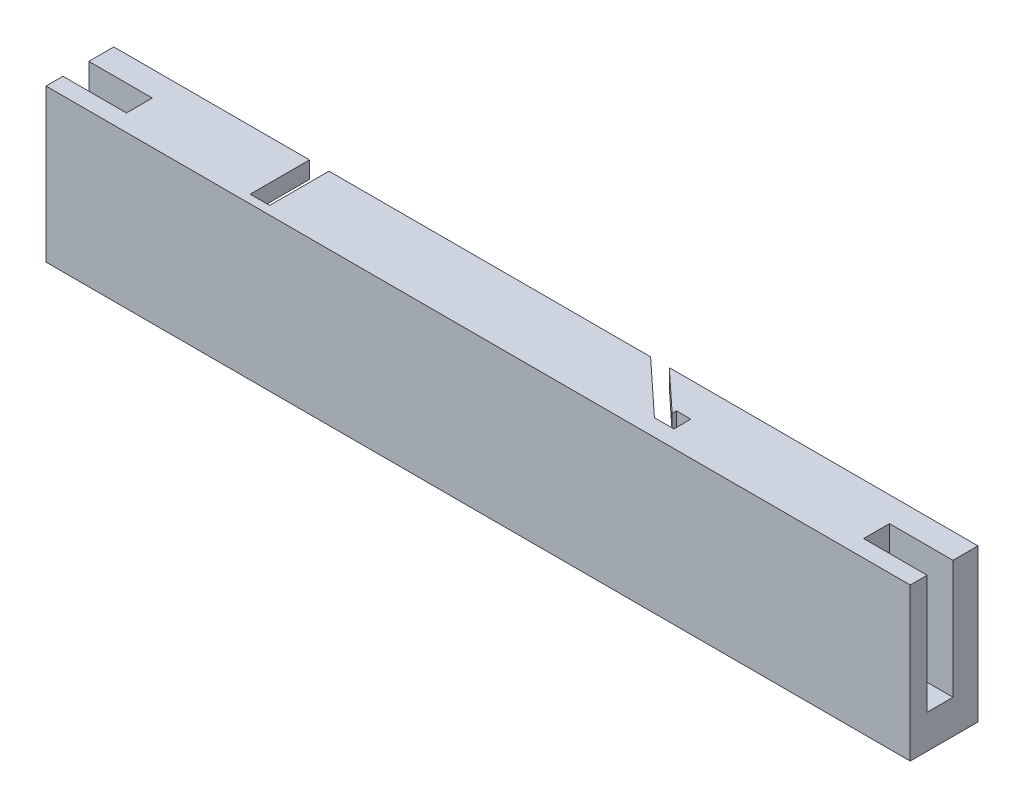
SolidWorks part; units mm, degrees
ref_plane "Front Plane" through (0, 0, 0) normal (0, 0, 1) x (1, 0, 0)
ref_plane "Top Plane" through (0, 0, 0) normal (0, 1, 0) x (1, 0, 0)
ref_plane "Right Plane" through (0, 0, 0) normal (1, 0, 0) x (0, 0, -1)
sketch "Sketch1" plane through (0, 0, 0) normal (0, 0, 1) x (1, 0, 0)
  line L1 (-51, -9) -> (51, -9)
  line L2 (-51, -9) -> (-51, 9)
  line L3 (-51, 9) -> (51, 9)
  line L4 (51, -9) -> (51, 9)
  line L5 (-51, -9) -> (51, 9) construction
  line L6 (-51, 9) -> (51, -9) construction
  point P0 (0, 0)
  dimension "D1" = 102
  dimension "D2" = 18
extrude "Boss-Extrude1" add sketch "Sketch1" along normal blind 2
sketch "Sketch2" plane through (0, 9, 0) normal (0, 1, 0) x (1, 0, 0)
  line L0 (0, -2) -> (0, 15.0089) construction
  line L1 (-51, -2) -> (-40.5, -2)
  line L2 (-51, -2) -> (-51, 6)
  line L3 (-51, 6) -> (-40.5, 6)
  line L4 (-40.5, -2) -> (-40.5, 6)
  line L5 (-51, 0) -> (-43.5, 0)
  line L6 (-51, 0) -> (-51, 3.05)
  line L7 (-51, 3.05) -> (-43.5, 3.05)
  line L8 (-43.5, 0) -> (-43.5, 3.05)
  line L9 (51, -2) -> (-51, -2) construction
  line L10 (43.5, 0) -> (43.5, 3.05)
  line L11 (51, 3.05) -> (43.5, 3.05)
  line L12 (51, 0) -> (51, 3.05)
  line L13 (51, 0) -> (43.5, 0)
  line L14 (40.5, -2) -> (40.5, 6)
  line L15 (51, 6) -> (40.5, 6)
  line L16 (51, -2) -> (51, 6)
  line L17 (51, -2) -> (40.5, -2)
  line M8 (51, 0) -> (-51, 0)
  dimension "D1" = 8
  dimension "D2" = 10.5
  dimension "D3" = 3.05
  dimension "D4" = 7.5
extrude "Boss-Extrude2" add sketch "Sketch2" against normal blind 18 contours L8 L4 L3 L2 L7 M8 | L11 L16 L15 L14 L10 M8
sketch "Sketch4" plane through (0, 0, 0) normal (0, 0, -1) x (-1, 0, 0)
  line L0 (40.5, -9) -> (40.5, 9) construction
  line L1 (-40.5, 9) -> (40.5, 9)
  line L2 (-40.5, 9) -> (-40.5, 7)
  line L3 (-40.5, 7) -> (40.5, 7)
  line L4 (40.5, 9) -> (40.5, 7)
  line L5 (40.5, -9) -> (40.5, 9) construction
  line L6 (-40.5, -9) -> (40.5, -9)
  line L7 (-40.5, -9) -> (-40.5, -7)
  line L8 (-40.5, -7) -> (40.5, -7)
  line L9 (40.5, -9) -> (40.5, -7)
  dimension "D1" = 2
  dimension "D2" = 2
extrude "Boss-Extrude3" add sketch "Sketch4" along normal blind 6
sketch "Sketch5" plane through (0, 0, -6) normal (0, 0, -1) x (-1, 0, 0)
  line L0 (40.5, -7) -> (-40.5, -7) construction
  line L1 (25.6, -7) -> (27.9, -7)
  line L2 (25.6, -7) -> (25.6, -9)
  line L3 (25.6, -9) -> (27.9, -9)
  line L4 (27.9, -7) -> (27.9, -9)
  line L5 (51, -9) -> (-51, -9) construction
  line L6 (51, -9) -> (51, 9) construction
  line L7 (-40.5, 7) -> (40.5, 7) construction
  line L8 (27.9, 7) -> (25.6, 7)
  line L9 (27.9, 7) -> (27.9, 9)
  line L10 (27.9, 9) -> (25.6, 9)
  line L11 (25.6, 7) -> (25.6, 9)
  line L12 (51, 9) -> (-51, 9) construction
  line L13 (-19.4, 7) -> (-19.4, 9)
  line L14 (-19.4, 7) -> (-21.1, 7)
  line L15 (-21.1, 7) -> (-21.1, 9)
  line L16 (-19.4, 9) -> (-21.1, 9)
  line L17 (-21.1, -7) -> (-19.4, -7)
  line L18 (-19.4, -7) -> (-19.4, -9)
  line L19 (-21.1, -9) -> (-19.4, -9)
  line L20 (-21.1, -7) -> (-21.1, -9)
  line L21 (26.75, 7) -> (26.75, -7) construction
  line L22 (-20.25, 7) -> (-20.25, -9) construction
  point P8 (26.75, -7)
  point P29 (26.75, 9)
  point P30 (-20.25, 9)
  point P33 (-20.25, -7)
  dimension "D1" = 2.3
  dimension "D2" = 24.25
  dimension "D4" = 1.7
  dimension "D3" = 1.7
  dimension "D5" = 2.3
  dimension "D6" = 47
  dimension "D7" = 2
extrude "Cut-Extrude1" cut sketch "Sketch5" against normal blind 6
sketch "Sketch6" plane through (0, 0, -6) normal (0, 0, -1) x (-1, 0, 0)
  line L1 (-21.1, 9) -> (-19.4, 9)
  line L2 (-21.1, 9) -> (-21.1, 7)
  line L3 (-21.1, 7) -> (-19.4, 7)
  line L4 (-19.4, 9) -> (-19.4, 7)
  line L5 (-21.1, -7) -> (-19.4, -7)
  line L6 (-21.1, -7) -> (-21.1, -9)
  line L7 (-21.1, -9) -> (-19.4, -9)
  line L8 (-19.4, -7) -> (-19.4, -9)
extrude "Boss-Extrude4" add sketch "Sketch6" against normal blind 4
sketch "Sketch7" plane through (0, 9, 0) normal (0, 1, 0) x (1, 0, 0)
  line L0 (18.8101, 0) -> (12.3617, 6)
  line L1 (-25.6, 6) -> (51, 6) construction
  line L2 (14.5637, 6) -> (19.4, 1.5)
  line L3 (19.4, 0) -> (19.4, 2) construction
  line L4 (19.4, 0) -> (21.1, 0) construction
  line L5 (20.0413, 0) -> (18.8101, 0)
  line L6 (20.0413, 0) -> (20.0413, 1.5)
  line L7 (20.0413, 1.5) -> (19.4, 1.5)
  line L10 (12.3617, 6) -> (14.5637, 6)
  point P0 (20.0413, 0)
  dimension "D1" = 1.5
  dimension "D3" = 1.5
extrude "Cut-Extrude2" cut sketch "Sketch7" against normal blind 20
sketch "Sketch8" plane through (0, 0, 0) normal (0, 0, -1) x (-1, 0, 0)
  line L0 (40.5, 0) -> (0, 0) construction
  line L1 (34.75, 3) -> (32.75, 3)
  line L2 (34.75, 3) -> (34.75, -3)
  line L3 (34.75, -3) -> (32.75, -3)
  line L4 (32.75, 3) -> (32.75, -3)
  line L5 (40.5, -7) -> (40.5, 7) construction
  line L6 (25.6, 8) -> (27.9, 8) construction
  line L7 (25.6, 9) -> (25.6, 7) construction
  line L8 (27.9, 7) -> (27.9, 9) construction
  line L9 (26.75, 8) -> (26.75, 0) construction
  point P17 (32.75, 0)
  dimension "D1" = 6
  dimension "D2" = 2
  dimension "D3" = 6
extrude "Boss-Extrude5" add sketch "Sketch8" along normal blind 1
sketch "Sketch10" plane through (0, 0, -1) normal (0, 0, -1) x (-1, 0, 0)
  line L1 (34.75, 3) -> (31.25, 3)
  line L2 (34.75, 3) -> (34.75, -3)
  line L3 (34.75, -3) -> (31.25, -3)
  line L4 (31.25, 3) -> (31.25, -3)
  dimension "D1" = 3.5
extrude "Boss-Extrude6" add sketch "Sketch10" along normal blind 1
sketch "Sketch11" plane through (0, 0, 0) normal (0, 0, -1) x (-1, 0, 0)
  line L0 (0, 0) -> (34.75, 0) construction
  line L1 (34.75, -3) -> (34.75, 3) construction
  line L2 (25.6, 8) -> (27.9, 8) construction
  line L3 (25.6, 9) -> (25.6, 7) construction
  line L4 (27.9, 7) -> (27.9, 9) construction
  line L5 (26.75, 8) -> (26.75, 0) construction
  line L7 (5.05, 3) -> (6.55, 3)
  line L8 (5.05, 3) -> (5.05, -3)
  line L9 (5.05, -3) -> (6.55, -3)
  line L10 (6.55, 3) -> (6.55, -3)
  point P17 (6.55, 0)
  dimension "D1" = 20.2
  dimension "D2" = 1.5
  dimension "D3" = 6
extrude "Boss-Extrude7" add sketch "Sketch11" along normal blind 8
sketch "Sketch12" plane through (0, -3, 0) normal (0, -1, 0) x (1, 0, 0)
  line L0 (-6.55, -8) -> (-7.55, -6)
  line L1 (-7.55, -6) -> (-6.55, -6)
  line L2 (-6.55, -8) -> (-6.55, 0) construction
  line L3 (-6.55, -8) -> (-6.55, -6)
  dimension "D1" = 1
  dimension "D2" = 2
extrude "Boss-Extrude8" add sketch "Sketch12" against normal blind 6
sketch "Sketch17" plane through (0, 0, 0) normal (0, 1, 0) x (1, 0, 0)
  line L0 (-5.05, 8) -> (1.95, 0)
  line L2 (-25.6, 0) -> (18.8101, 0) construction
  line L3 (-5.05, 8) -> (-5.05, 0) construction
  dimension "D1" = 7
rib "Rib1" sketch "Sketch17" sketch "Sketch17" thickness 4 extrusion direction parallel to sketch draft on no parameters "D1"=4
chamfer "Chamfer1" distance 0.5 angle 45 1 edges at (-31.25, 0, -1)
sketch "Sketch18" plane through (0, -9, 0) normal (0, -1, 0) x (1, 0, 0)
  line L1 (43.5, -3.05) -> (51, -3.05)
  line L2 (43.5, -3.05) -> (43.5, 0)
  line L3 (43.5, 0) -> (51, 0)
  line L4 (51, -3.05) -> (51, 0)
  line L5 (-43.5, -3.05) -> (-51, -3.05)
  line L6 (-43.5, -3.05) -> (-43.5, 0)
  line L7 (-43.5, 0) -> (-51, 0)
  line L8 (-51, -3.05) -> (-51, 0)
extrude "Boss-Extrude10" add sketch "Sketch18" against normal blind 4
sketch "Sketch19" plane through (0, 0, 0) normal (0, 0, -1) x (-1, 0, 0)
  line L0 (6.55, 0) -> (32.7255, 0) construction
  line L1 (6.55, -3) -> (6.55, 3) construction
  line L4 (6.55, -5.5) -> (32.7255, -5.5)
  line L5 (6.55, -5.5) -> (6.55, 5.5)
  line L6 (6.55, 5.5) -> (32.7255, 5.5)
  line L7 (32.7255, -5.5) -> (32.7255, 5.5)
  line L8 (6.55, -5.5) -> (32.7255, 5.5) construction
  line L9 (6.55, 5.5) -> (32.7255, -5.5) construction
  point P5 (19.6377, 0)
  dimension "D1" = 11
extrude "Cut-Extrude3" cut sketch "Sketch19" against normal blind 1
sketch "Sketch20" plane through (0, 9, 0) normal (0, 1, 0) x (1, 0, 0)
  line L0 (-27.9, 0) -> (-25.6, 0)
  line L1 (-25.6, 0) -> (-25.6, -1)
  line L2 (-25.6, -1) -> (-27.9, -1)
  line L3 (-27.9, -1) -> (-27.9, 0)
  dimension "D1" = 1
extrude "Cut-Extrude4" cut sketch "Sketch20" against normal blind 21
